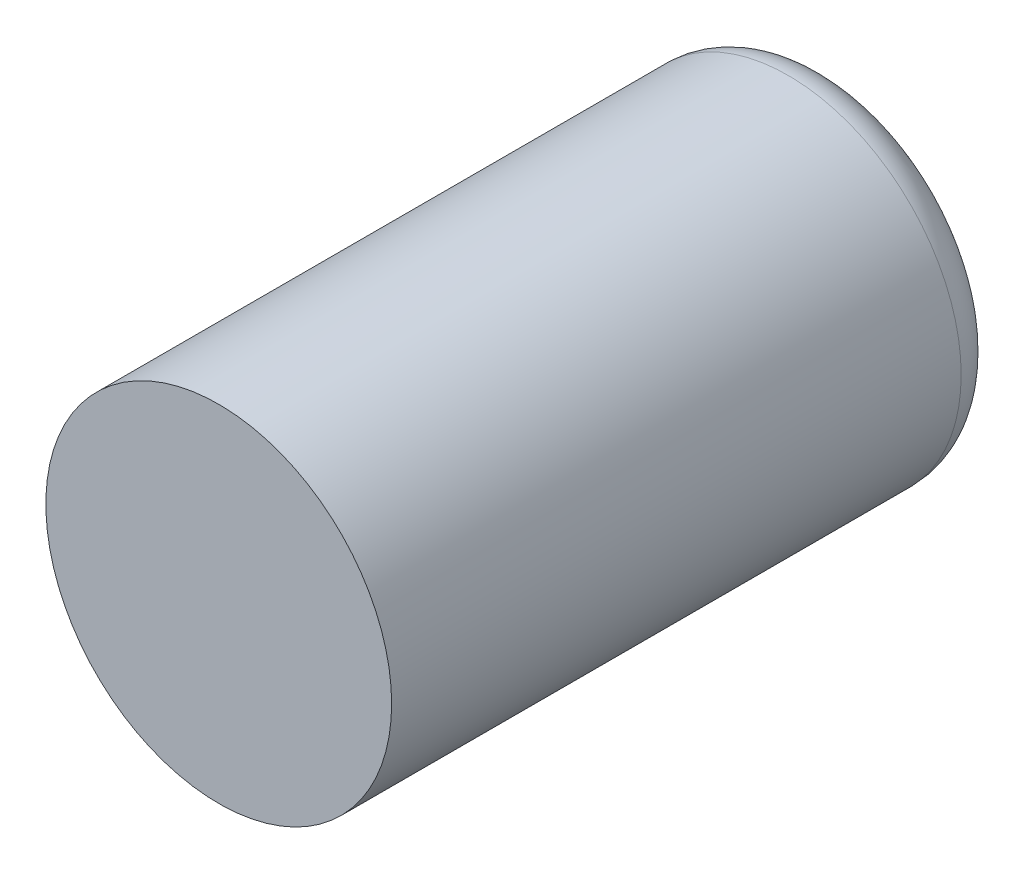
SolidWorks part; units mm, degrees
ref_plane "Front Plane" through (0, 0, 0) normal (0, 0, 1) x (1, 0, 0)
ref_plane "Top Plane" through (0, 0, 0) normal (0, 1, 0) x (1, 0, 0)
ref_plane "Right Plane" through (0, 0, 0) normal (1, 0, 0) x (0, 0, -1)
sketch "Sketch1" plane through (0, 0, 0) normal (0, 1, 0) x (1, 0, 0)
  line L0 (6.5, 0) -> (0, 0)
  line L1 (0, 0) -> (0, -30)
  line L2 (0, -30) -> (8.5, -30)
  line L3 (8.5, -30) -> (8.5, -2)
  line L4 (0, 0.0013) -> (0, -30) construction
  arc A0 (8.5, -2) -> (6.5, 0) centre (6.5, -2) ccw
revolve "Revolve1" add sketch "Sketch1" angle 360 about L4
